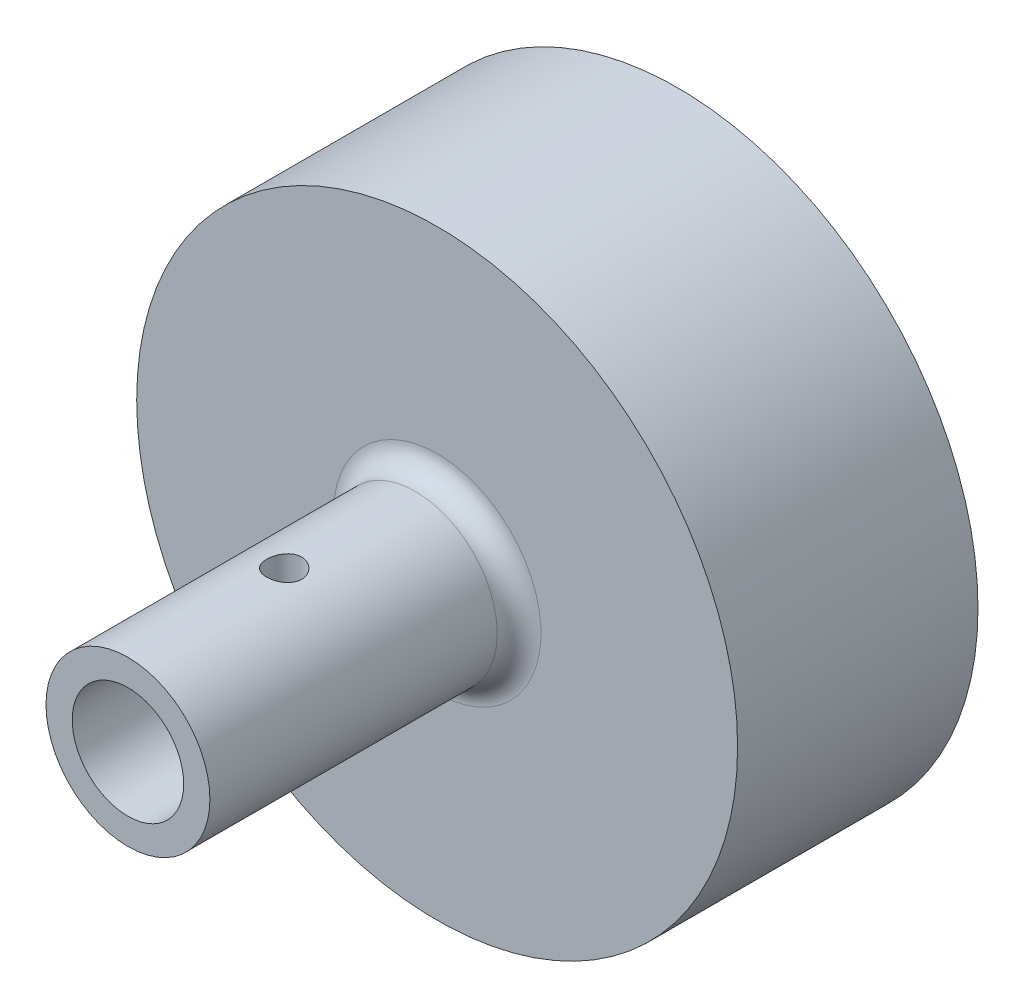
SolidWorks part; units mm, degrees
ref_plane "Front Plane" through (0, 0, 0) normal (0, 0, 1) x (1, 0, 0)
ref_plane "Top Plane" through (0, 0, 0) normal (0, 1, 0) x (1, 0, 0)
ref_plane "Right Plane" through (0, 0, 0) normal (1, 0, 0) x (0, 0, -1)
sketch "Sketch1" plane through (0, 0, 0) normal (0, 0, 1) x (1, 0, 0)
  circle A0 centre (0, 0) radius 7.5
  circle A1 centre (0, 0) radius 5.1
  dimension "D1" = 15
  dimension "D2" = 10.2
extrude "Boss-Extrude1" add sketch "Sketch1" along normal blind 28.3
sketch "Sketch4" plane through (0, 0, 0) normal (0, 0, -1) x (-1, 0, 0)
  circle A0 centre (0, 0) radius 27.5
  dimension "D1" = 55
extrude "Boss-Extrude3" add sketch "Sketch4" along normal blind 22
fillet "Fillet1" radius 2 1 edges at (7.5, 0, 0)
sketch "Sketch5" plane through (0, 0, -22) normal (0, 0, -1) x (-1, 0, 0)
  circle A8 centre (0, 12) radius 2.125
  circle A9 centre (12, 0) radius 2.125
  circle A10 centre (0, -12) radius 2.125
  circle A11 centre (-12, 0) radius 2.125
  point P11 (0, 0)
  dimension "D1" = 4.25
  dimension "D2" = 12
  dimension "D3" = 4
extrude "Cut-Extrude2" cut sketch "Sketch5" against normal blind 20
sketch "Sketch6" plane through (0, 0, 0) normal (0, 0, 1) x (1, 0, 0)
  line L0 (-3.1639, 4) -> (3.1639, 4)
  circle A0 centre (0, 0) radius 5.1 construction
  arc A1 (-3.1639, 4) -> (3.1639, 4) centre (0, 0) cw
  circle M2 centre (0, 0) radius 5.1
  dimension "D1" = 4
extrude "Boss-Extrude4" add sketch "Sketch6" along normal blind 20 contours L0 M2
sketch "Sketch7" plane through (0, 0, 0) normal (0, 1, 0) x (1, 0, 0)
  line L0 (7.5, -28.3) -> (7.5, -2) construction
  line L1 (-27.5, 0) -> (27.5, 0) construction
  circle A0 centre (0, -14) radius 1.6
  dimension "D1" = 3.2
  dimension "D2" = 7.5
  dimension "D3" = 14
extrude "Cut-Extrude3" cut sketch "Sketch7" along normal blind 15
